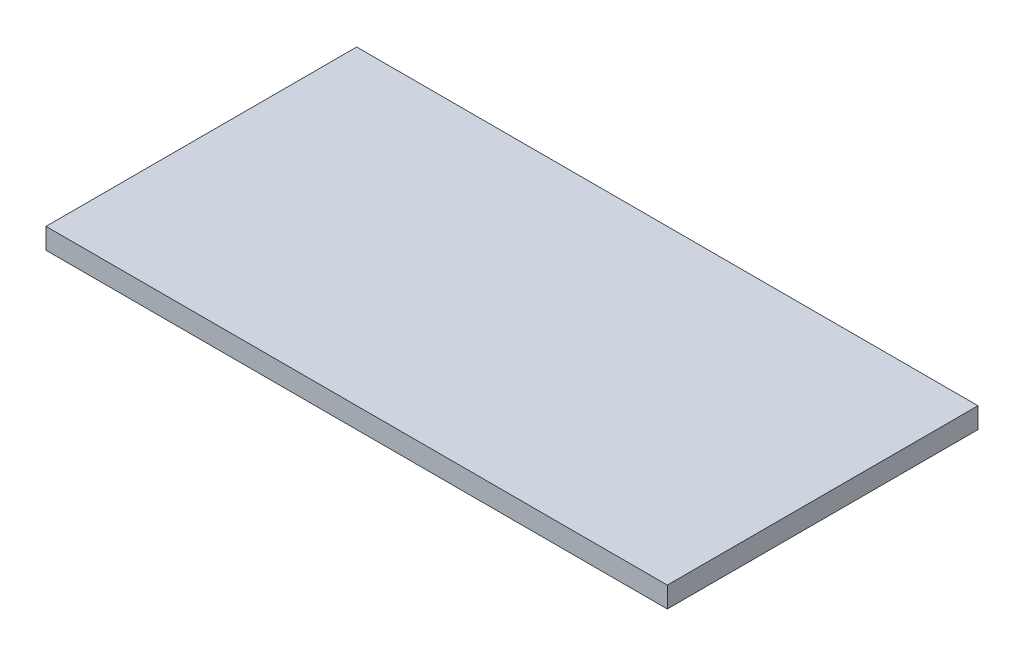
SolidWorks part; units mm, degrees
ref_plane "前视基准面" through (0, 0, 0) normal (0, 0, 1) x (1, 0, 0)
ref_plane "上视基准面" through (0, 0, 0) normal (0, 1, 0) x (1, 0, 0)
ref_plane "右视基准面" through (0, 0, 0) normal (1, 0, 0) x (0, 0, -1)
sketch "草图1" plane through (0, 0, 0) normal (0, 1, 0) x (1, 0, 0)
  line L1 (-300, 150) -> (300, 150)
  line L2 (-300, 150) -> (-300, -150)
  line L3 (-300, -150) -> (300, -150)
  line L4 (300, 150) -> (300, -150)
  line L5 (-300, 150) -> (300, -150) construction
  line L6 (-300, -150) -> (300, 150) construction
  point P0 (0, 0)
extrude "凸台-拉伸1" add sketch "草图1" along normal blind 20
